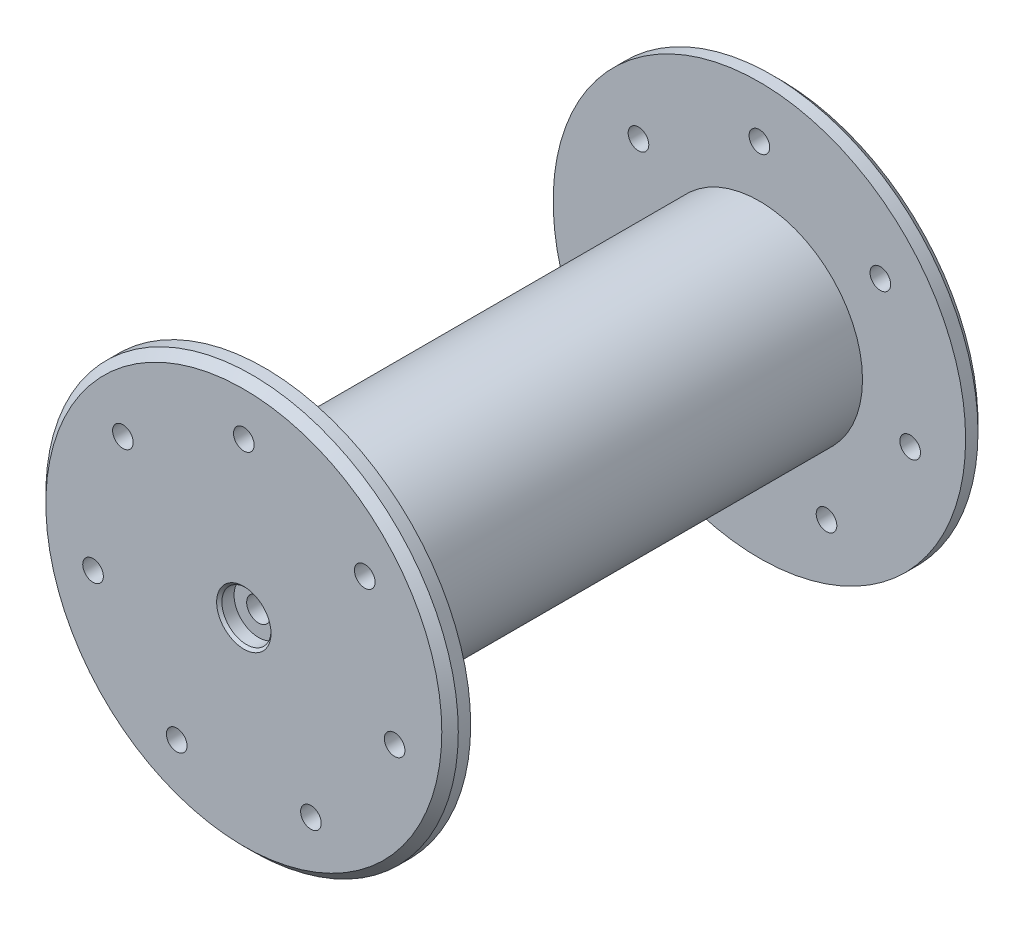
SolidWorks part; units mm, degrees
ref_plane "Front Plane" through (0, 0, 0) normal (0, 0, 1) x (1, 0, 0)
ref_plane "Top Plane" through (0, 0, 0) normal (0, 1, 0) x (1, 0, 0)
ref_plane "Right Plane" through (0, 0, 0) normal (1, 0, 0) x (0, 0, -1)
sketch "Sketch2" plane through (0, 0, 0) normal (0, 0, 1) x (1, 0, 0)
  circle A0 centre (0, 0) radius 25
  dimension "ShaftDiameter" = 50
extrude "Boss-Extrude1" add sketch "Sketch2" along normal mid plane 120
sketch "Sketch3" plane through (0, 0, 60) normal (0, 0, 1) x (1, 0, 0)
  circle A0 centre (0, 0) radius 50
  dimension "CapDiameter" = 100
extrude "Boss-Extrude2" add sketch "Sketch3" along normal blind 5
chamfer "Chamfer1" distance 2 angle 45 1 edges at (50, 0, 65)
sketch "Sketch4" plane through (0, 0, 65) normal (0, 0, 1) x (1, 0, 0)
  line L0 (0, 25) -> (0, 50) construction
  circle A0 centre (0, 0) radius 25 construction
  circle A1 centre (0, 0) radius 50 construction
  circle A2 centre (0, 37.5) radius 2.5
  dimension "D1" = 5
extrude "Cut-Extrude1" cut sketch "Sketch4" against normal through all contours A2
pattern_circular "CirPattern1" count 7 over 360 about axis through (0, 0, 0) along (0, 0, 1) of "Cut-Extrude1"
hole_wizard "CBORE for #12 Binding Head Machine Screw1" positions "Sketch5" profile "Sketch6" counterbore size "#12" standard "ANSI Inch" end condition through all
sketch "Sketch5" plane through (0, 0, 65) normal (0, 0, 1) x (1, 0, 0)
  point P0 (0, 0)
sketch "Sketch6" plane through (0, 0, 65) normal (1, 0, 0) x (0, -1, 0)
  line L0 (0, 0) -> (0, 130)
  line L1 (0, 130) -> (2.8956, 130)
  line L3 (2.8956, 130) -> (2.8956, 3.5814)
  line L4 (5.9538, 3.5814) -> (2.8956, 3.5814)
  line L5 (5.9538, 3.5814) -> (5.9538, 0.635)
  line L6 (5.9538, 0.635) -> (6.5888, 0)
  line L7 (6.5888, 0) -> (0, 0)
  line L8 (-5.9538, 0.635) -> (-6.5888, 0) construction
  line L11 (0, -6.35) -> (0, 107.95) construction
  dimension "Thru Hole Dia." = 5.7912
  dimension "Thru Hole Depth" = 130
  dimension "C'Bore Dia." = 11.9075
  dimension "C'Bore Depth" = 3.5814
  dimension "Near C'Sink Dia." = 13.1775
  dimension "Near C'Sink Angle" = 90
mirror "Mirror1" about plane through (0, 0, 0) normal (0, 0, 1) of "CBORE for #12 Binding Head Machine Screw1", "CirPattern1", "Cut-Extrude1", "Chamfer1", "Boss-Extrude2"
